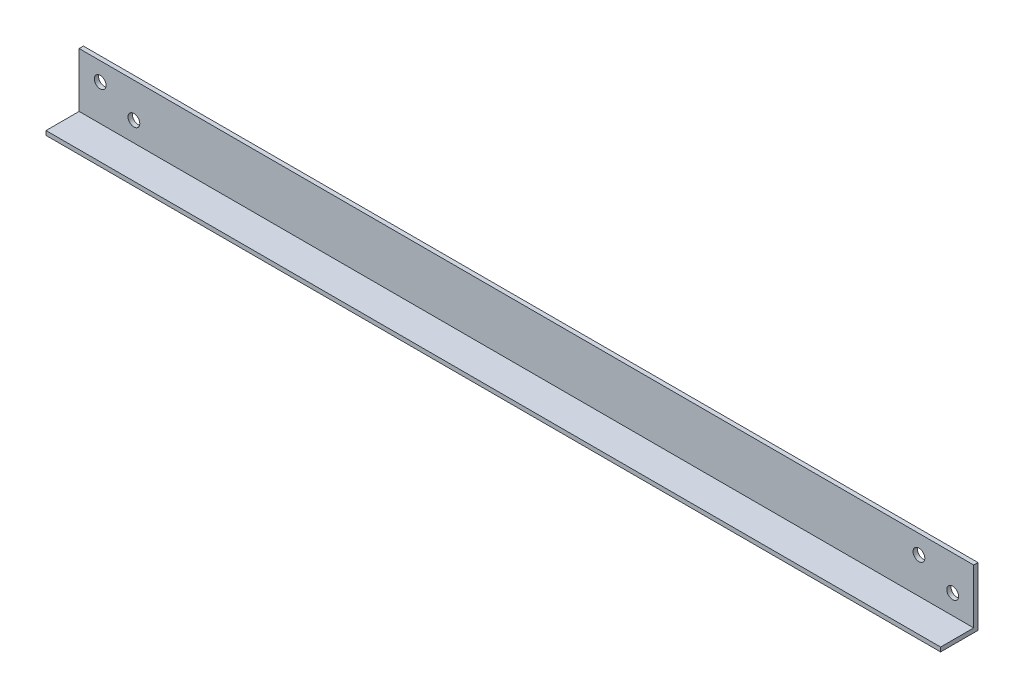
SolidWorks part; units mm, degrees
ref_plane "前视基准面" through (0, 0, 0) normal (0, 0, 1) x (1, 0, 0)
ref_plane "上视基准面" through (0, 0, 0) normal (0, 1, 0) x (1, 0, 0)
ref_plane "右视基准面" through (0, 0, 0) normal (1, 0, 0) x (0, 0, -1)
sketch "草图1" plane through (0, 0, 0) normal (0, 0, 1) x (1, 0, 0)
  line L1 (0, 0) -> (1675, 0)
  line L2 (0, 0) -> (0, 110)
  line L3 (0, 110) -> (1675, 110)
  line L4 (1675, 0) -> (1675, 110)
  dimension "D1" = 1675
  dimension "D2" = 110
extrude "拉伸1" add sketch "草图1" along normal blind 8
sketch "草图2" plane through (0, 0, 8) normal (0, 0, 1) x (1, 0, 0)
  line L1 (0, 0) -> (1675, 0)
  line L2 (0, 0) -> (0, 8)
  line L3 (0, 8) -> (1675, 8)
  line L4 (1675, 0) -> (1675, 8)
  dimension "D1" = 1675
  dimension "D2" = 8
extrude "拉伸2" add sketch "草图2" along normal blind 62
sketch "草图3" plane through (0, 0, 0) normal (0, 0, -1) x (-1, 0, 0)
  line L1 (0, 0) -> (-1675, 0) construction
  circle A0 centre (-1635.5748, 45) radius 11
  circle A1 centre (-1572.4073, 75.1641) radius 11
  circle A2 centre (-102.5927, 45) radius 11
  circle A3 centre (-39.4252, 75.1641) radius 11
  point P13 (-837.5, 0)
  dimension "D1" = 1596.1495
  dimension "D2" = 70
  dimension "D3" = 70
  dimension "D4" = 45
  dimension "D5" = 30.1641
  dimension "D6" = 798.0748
extrude "切除-拉伸1" cut sketch "草图3" against normal through all
